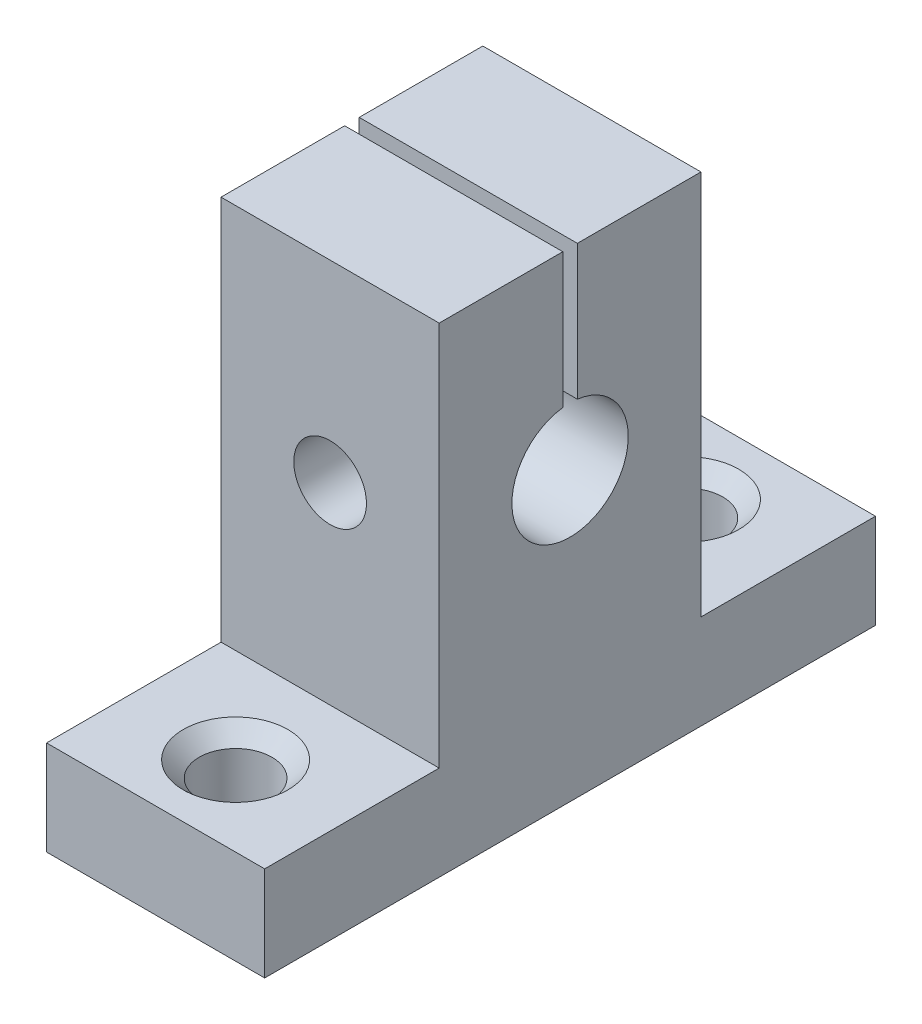
SolidWorks part; units mm, degrees
ref_plane "Front Plane" through (0, 0, 0) normal (0, 0, 1) x (1, 0, 0)
ref_plane "Top Plane" through (0, 0, 0) normal (0, 1, 0) x (1, 0, 0)
ref_plane "Right Plane" through (0, 0, 0) normal (1, 0, 0) x (0, 0, -1)
sketch "Sketch1" plane through (0, 0, 0) normal (1, 0, 0) x (0, 0, -1)
  line L0 (0, 0) -> (42, 0)
  line L1 (42, 0) -> (42, 6.5)
  line L2 (42, 6.5) -> (30, 6.5)
  line L3 (30, 6.5) -> (30, 33)
  line L4 (30, 33) -> (21.5, 33)
  line L5 (12, 33) -> (12, 6.5)
  line L6 (12, 6.5) -> (0, 6.5)
  line L7 (0, 6.5) -> (0, 0)
  line L8 (20.5, 33) -> (20.5, 23.7186)
  line L9 (21.5, 33) -> (21.5, 23.7186)
  line L10 (20.5, 33) -> (12, 33)
  arc A0 (20.5, 23.7186) -> (21.5, 23.7186) centre (21, 19.75) ccw
  dimension "D1" = 8
  dimension "D2" = 42
  dimension "D3" = 33
  dimension "D4" = 6.5
  dimension "D5" = 12
  dimension "D6" = 13.25
  dimension "D8" = 1
  dimension "D7" = 9
  dimension "D9" = 9
  dimension "D10" = 12
  dimension "D11" = 19.75
extrude "ProfileBoss-Extrude1" add sketch "Sketch1" along normal blind 15
sketch "Sketch2" plane through (0, 6.5, 0) normal (0, 1, 0) x (1, 0, 0)
  line L0 (15, 0) -> (0, 0) construction
  line L1 (15, 42) -> (0, 42) construction
  line L2 (0, 12) -> (0, 0) construction
  circle A0 centre (7.5, 5.5) radius 2.5
  circle A1 centre (7.5, 36.5) radius 2.5
  dimension "D1" = 5
  dimension "D2" = 5.5
  dimension "D3" = 5.5
  dimension "D4" = 7.5
  dimension "D5" = 31
extrude "MountHolesCut-Extrude1" cut sketch "Sketch2" against normal through all
chamfer "Chamfer1" distance 1.1 angle 45 2 edges at (7.5, 6.5, -3) (7.5, 6.5, -34)
sketch "Sketch3" plane through (0, 0, -12) normal (0, 0, 1) x (1, 0, 0)
  line L0 (15, 19.75) -> (0, 19.75) construction
  circle A0 centre (7.5, 19.75) radius 2.5
  dimension "D1" = 5
extrude "GrommetHoleCut-Extrude2" cut sketch "Sketch3" against normal up to next
equation "\"SK8RodShaftDiameter\"= 8mm"
equation "\"SK8RodShaftSupportWidth\"= 33mm"
equation "\"D3@Sketch1\"=\"SK8RodShaftSupportWidth\""
equation "\"SK8RodShaftSupportHeight\"= 42mm"
equation "\"SK8RodShaftSupportLength\"= 15mm"
equation "\"SK8MountHoleDiameter\"= 5mm"
equation "\"SK8MountTabHeight\"= 12mm"
equation "\"SK8MountTabWidth\"= 6.5mm"
equation "\"D6@Sketch1\"=(\"SK8RodShaftSupportWidth\" - \"SK8MountTabWidth\")/2"
equation "\"D2@Sketch2\"=\"SK8MountHoleFromEitherEnd\""
equation "\"D3@Sketch2\"=\"SK8MountHoleFromEitherEnd\""
equation "\"D1@Sketch2\"=\"SK8MountHoleDiameter\""
equation "\"D4@Sketch1\"=\"SK8MountTabWidth\""
equation "\"D5@Sketch1\"=\"SK8MountTabHeight\""
equation "\"D2@Sketch1\"=\"SK8RodShaftSupportHeight\""
equation "\"SK8MountHoleFromSide\"= \"SK8RodShaftSupportLength\" / 2"
equation "\"D1@Sketch1\"=\"SK8RodShaftDiameter\""
equation "\"D4@Sketch2\"=\"SK8MountHoleFromSide\""
equation "\"SK8MountHoleFromEitherEnd\"= 5.5mm"
equation "\"SK8ClampHeight\"= 18mm"
equation "\"D7@Sketch1\"=\"SK8ClampHeight\"/2"
